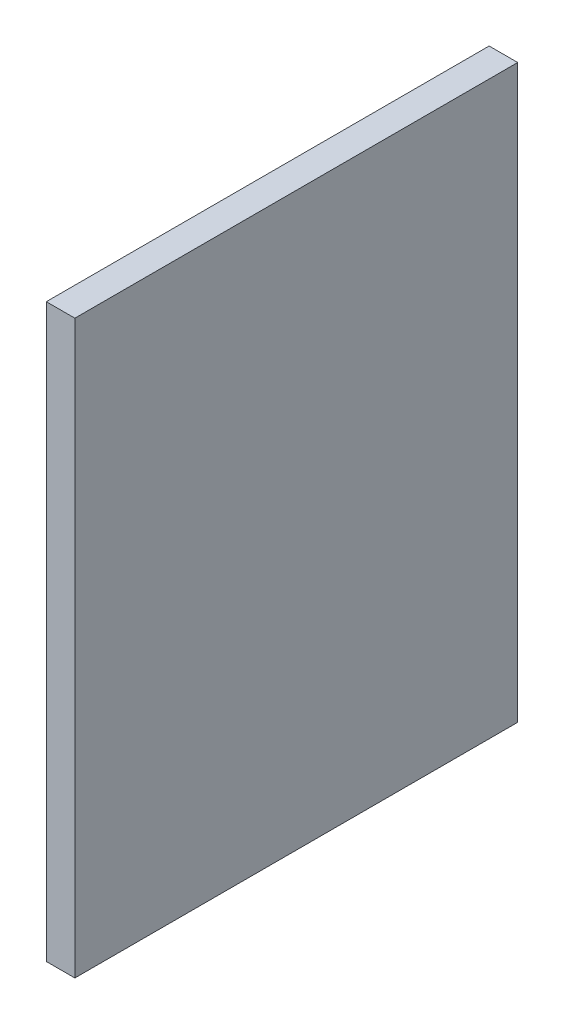
SolidWorks part; units mm, degrees
ref_plane "Alzado" through (0, 0, 0) normal (0, 0, 1) x (1, 0, 0)
ref_plane "Planta" through (0, 0, 0) normal (0, 1, 0) x (1, 0, 0)
ref_plane "Vista lateral" through (0, 0, 0) normal (1, 0, 0) x (0, 0, -1)
ref_plane "Plano_CajaSujetadoraEste" through (0, 630, 0) normal (0, 1, 0) x (1, 0, 0)
sketch "SkCajaSujetadoraEste" plane through (0, 630, 0) normal (0, 1, 0) x (1, 0, 0)
  line L1 (135, -155) -> (155, -155)
  line L2 (135, -155) -> (135, 155)
  line L3 (135, 155) -> (155, 155)
  line L4 (155, -155) -> (155, 155)
extrude "CajaSujetadoraEste" add sketch "SkCajaSujetadoraEste" along normal blind 400 separate body
